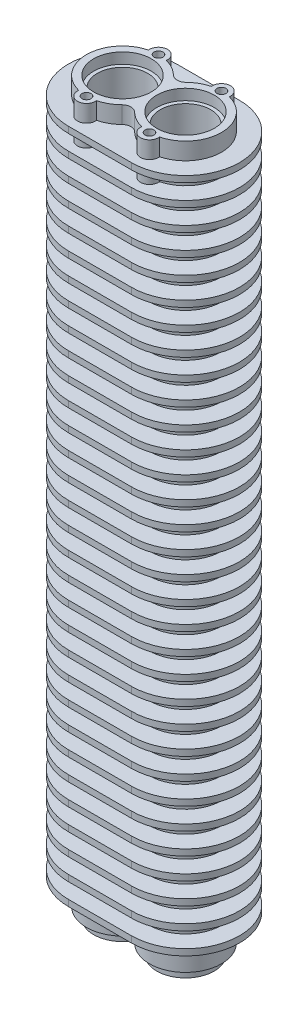
SolidWorks part; units mm, degrees
material "1060 Alloy"
ref_plane "Front Plane" through (0, 0, 0) normal (0, 0, 1) x (1, 0, 0)
ref_plane "Top Plane" through (0, 0, 0) normal (0, 1, 0) x (1, 0, 0)
ref_plane "Right Plane" through (0, 0, 0) normal (1, 0, 0) x (0, 0, -1)
sketch "Sketch2" plane through (0, 0, 0) normal (0, 1, 0) x (1, 0, 0)
  arc A0 (14, 14.2829) -> (14, -14.2829) centre (0, 0) ccw
  arc A1 (21, -14.2829) -> (21, 14.2829) centre (35, 0) ccw
  circle A2 centre (0, 0) radius 14
  circle A3 centre (35, 0) radius 14
  arc A4 (21, 14.2829) -> (14, 14.2829) centre (17.5, 17.8536) cw
  arc A5 (21, -14.2829) -> (14, -14.2829) centre (17.5, -17.8536) ccw
  dimension "D1" = 40
  dimension "D2" = 40
  dimension "D4" = 28
  dimension "D5" = 28
  dimension "D6" = 5
  dimension "D7" = 5
  dimension "D3" = 35
extrude "Extrude1" add sketch "Sketch2" along normal blind 400
ref_plane "Plane1" through (0, 15, 0) normal (0, -1, 0) x (1, 0, 0)
sketch "Sketch3" plane through (0, 15, 0) normal (0, -1, 0) x (1, 0, 0)
  line L0 (0, 30) -> (35, 30)
  line L1 (35, -30) -> (0, -30)
  arc A0 (0, 30) -> (0, -30) centre (0, 0) ccw
  arc A1 (35, -30) -> (35, 30) centre (35, 0) ccw
  dimension "D1" = 30
  dimension "D2" = 30
  dimension "D3" = 35
extrude "Extrude2" add sketch "Sketch3" against normal blind 3.5
pattern_linear "LPattern1" count 32 spacing 12 along (0, 1, 0) of "Extrude2"
sketch "Sketch4" plane through (0, 390.5, 0) normal (0, 1, 0) x (1, 0, 0)
  circle A0 centre (0, 0) radius 14
  circle A1 centre (35, 0) radius 14
  dimension "D1" = 28
  dimension "D2" = 28
extrude "Cut-Extrude1" cut sketch "Sketch4" against normal through all
sketch "Sketch5" plane through (0, 400, 0) normal (0, 1, 0) x (1, 0, 0)
  line L0 (35, 0) -> (35, -34.0055) construction
  line L1 (35, 0) -> (35, 36.6213) construction
  line L2 (0, 0) -> (0, 39.6987) construction
  line L3 (0, 0) -> (0, -37.6676) construction
  circle A0 centre (0, 20) radius 5
  circle A1 centre (35, 20) radius 5
  circle A2 centre (35, -20) radius 5
  circle A3 centre (0, -20) radius 5
  dimension "D1" = 10
  dimension "D2" = 10
  dimension "D3" = 10
  dimension "D4" = 10
extrude "Extrude3" add sketch "Sketch5" against normal up to surface (21.5 mm away)
hole_wizard "M6 Tapped Hole2" positions "Sketch7" profile "Sketch6" tap size "M6" standard "ISO"
sketch "Sketch7" plane through (0, 400, 0) normal (0, 1, 0) x (-1, 0, 0)
  point P0 (0, -20)
sketch "Sketch6" plane through (0, 400, -20) normal (1, 0, 0) x (0, 0, 1)
  line L0 (0, 0) -> (0, 19.5022)
  line L1 (0, 19.5022) -> (2.5, 18)
  line L2 (2.5, 18) -> (2.5, 0)
  line L5 (2.5, 0) -> (0, 0)
  line L10 (0, 19.5022) -> (-2.5, 18) construction
  line L11 (0, -6.35) -> (0, 107.95) construction
  dimension "Tap Drill Dia." = 5
  dimension "Tap Drill Depth" = 18
  dimension "Drill Angle" = 118
cosmetic thread "Hole Thread1" parameters "D1"=12, "D2"=6
hole_wizard "M6 Tapped Hole3" positions "Sketch9" profile "Sketch8" tap size "M6" standard "ISO"
sketch "Sketch9" plane through (0, 400, 0) normal (0, 1, 0) x (-1, 0, 0)
  point P0 (0, 20)
sketch "Sketch8" plane through (0, 400, 20) normal (1, 0, 0) x (0, 0, 1)
  line L0 (0, 0) -> (0, 19.5022)
  line L1 (0, 19.5022) -> (2.5, 18)
  line L2 (2.5, 18) -> (2.5, 0)
  line L5 (2.5, 0) -> (0, 0)
  line L10 (0, 19.5022) -> (-2.5, 18) construction
  line L11 (0, -6.35) -> (0, 107.95) construction
  dimension "Tap Drill Dia." = 5
  dimension "Tap Drill Depth" = 18
  dimension "Drill Angle" = 118
cosmetic thread "Hole Thread2" parameters "D1"=12, "D2"=6
hole_wizard "M6 Tapped Hole4" positions "Sketch14" profile "Sketch13" tap size "M6" standard "ISO"
sketch "Sketch14" plane through (0, 400, 0) normal (0, 1, 0) x (-1, 0, 0)
  point P0 (-35, 20)
sketch "Sketch13" plane through (35, 400, 20) normal (1, 0, 0) x (0, 0, 1)
  line L0 (0, 0) -> (0, 19.5022)
  line L1 (0, 19.5022) -> (2.5, 18)
  line L2 (2.5, 18) -> (2.5, 0)
  line L5 (2.5, 0) -> (0, 0)
  line L10 (0, 19.5022) -> (-2.5, 18) construction
  line L11 (0, -6.35) -> (0, 107.95) construction
  dimension "Tap Drill Dia." = 5
  dimension "Tap Drill Depth" = 18
  dimension "Drill Angle" = 118
cosmetic thread "Hole Thread3" parameters "D1"=12, "D2"=6
hole_wizard "M6 Tapped Hole5" positions "Sketch18" profile "Sketch17" tap size "M6" standard "ISO"
sketch "Sketch18" plane through (0, 400, 0) normal (0, 1, 0) x (-1, 0, 0)
  point P0 (-35, -20)
sketch "Sketch17" plane through (35, 400, -20) normal (1, 0, 0) x (0, 0, 1)
  line L0 (0, 0) -> (0, 19.5022)
  line L1 (0, 19.5022) -> (2.5, 18)
  line L2 (2.5, 18) -> (2.5, 0)
  line L5 (2.5, 0) -> (0, 0)
  line L10 (0, 19.5022) -> (-2.5, 18) construction
  line L11 (0, -6.35) -> (0, 107.95) construction
  dimension "Tap Drill Dia." = 5
  dimension "Tap Drill Depth" = 18
  dimension "Drill Angle" = 118
cosmetic thread "Hole Thread4" parameters "D1"=12, "D2"=6
sketch "Sketch19" plane through (0, 400, 0) normal (0, 1, 0) x (1, 0, 0)
  circle A0 centre (0, 0) radius 16
  circle A1 centre (35, 0) radius 16
  dimension "D1" = 32
  dimension "D2" = 32
extrude "Cut-Extrude2" cut sketch "Sketch19" against normal blind 6
sketch "Sketch20" plane through (0, 0, 0) normal (0, -1, 0) x (1, 0, 0)
  circle A0 centre (0, 0) radius 16
  circle A1 centre (35, 0) radius 16
  circle A2 centre (0, 0) radius 14
  circle A3 centre (35, 0) radius 14
  dimension "D1" = 32
  dimension "D2" = 32
  dimension "D3" = 28
  dimension "D4" = 28
extrude "Extrude4" add sketch "Sketch20" along normal blind 5.5
